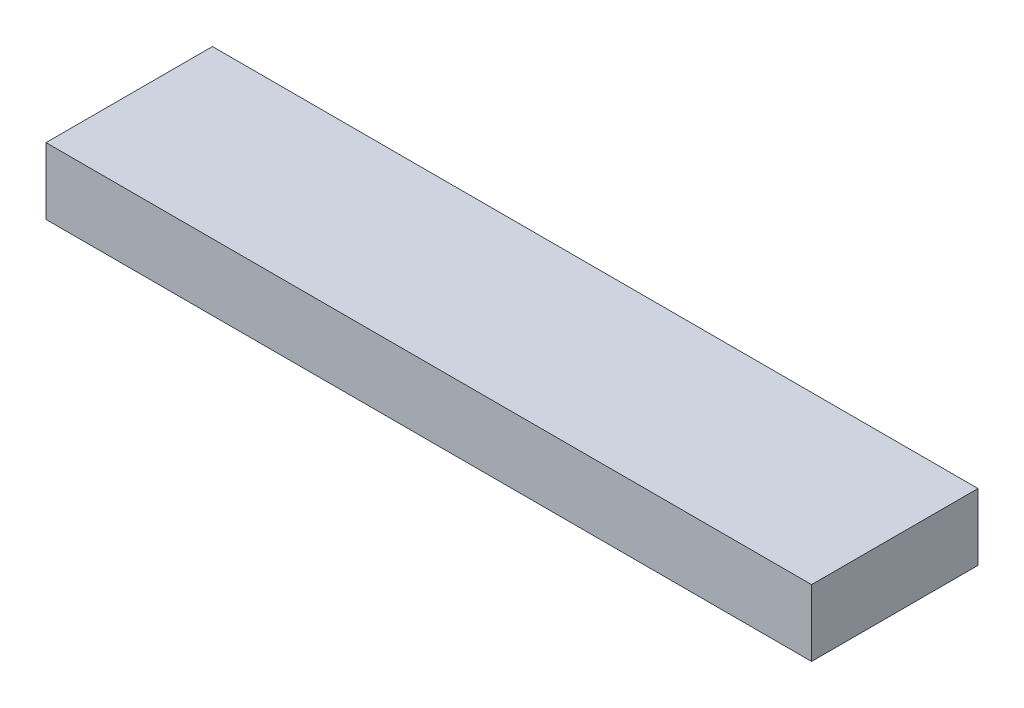
SolidWorks part; units mm, degrees
ref_plane "Front Plane" through (0, 0, 0) normal (0, 0, 1) x (1, 0, 0)
ref_plane "Top Plane" through (0, 0, 0) normal (0, 1, 0) x (1, 0, 0)
ref_plane "Right Plane" through (0, 0, 0) normal (1, 0, 0) x (0, 0, -1)
sketch "Sketch1" plane through (0, 0, 0) normal (0, 0, 1) x (1, 0, 0)
  line L1 (0, 0) -> (146.05, 0)
  line L2 (0, 0) -> (0, -12.7)
  line L3 (0, -12.7) -> (146.05, -12.7)
  line L4 (146.05, 0) -> (146.05, -12.7)
  dimension "D1" = 146.05
  dimension "D2" = 12.7
extrude "Extrude1" add sketch "Sketch1" along normal blind 31.75
